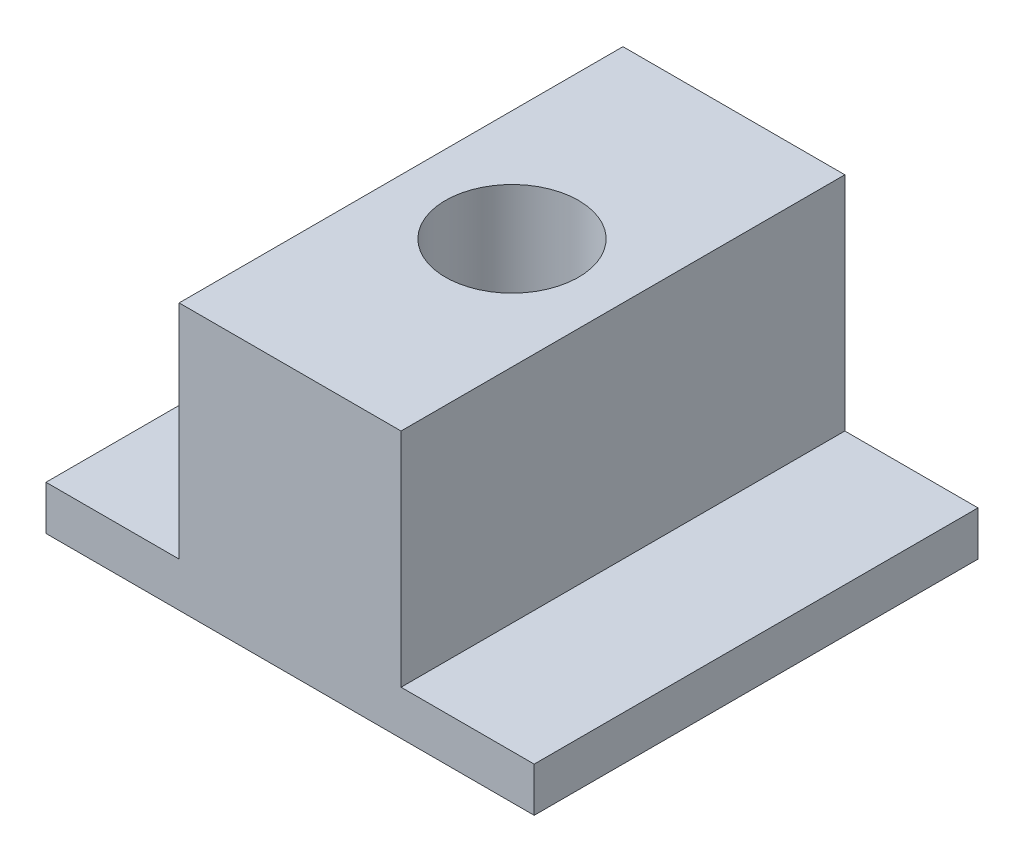
SolidWorks part; units mm, degrees
ref_plane "Front Plane" through (0, 0, 0) normal (0, 0, 1) x (1, 0, 0)
ref_plane "Top Plane" through (0, 0, 0) normal (0, 1, 0) x (1, 0, 0)
ref_plane "Right Plane" through (0, 0, 0) normal (1, 0, 0) x (0, 0, -1)
sketch "Sketch1" plane through (0, 0, 0) normal (0, 1, 0) x (1, 0, 0)
  line L1 (-2.5, -5) -> (2.5, -5)
  line L2 (-2.5, -5) -> (-2.5, 5)
  line L3 (-2.5, 5) -> (2.5, 5)
  line L4 (2.5, -5) -> (2.5, 5)
  line L5 (-2.5, -5) -> (2.5, 5) construction
  line L6 (-2.5, 5) -> (2.5, -5) construction
  point P0 (0, 0)
  dimension "D1" = 5
  dimension "D2" = 10
extrude "Boss-Extrude1" add sketch "Sketch1" along normal blind 5
sketch "Sketch2" plane through (0, 0, 0) normal (0, -1, 0) x (1, 0, 0)
  line L1 (-5.5, 5) -> (5.5, 5)
  line L2 (-5.5, 5) -> (-5.5, -5)
  line L3 (-5.5, -5) -> (5.5, -5)
  line L4 (5.5, 5) -> (5.5, -5)
  line L5 (-5.5, 5) -> (5.5, -5) construction
  line L6 (-5.5, -5) -> (5.5, 5) construction
  point P0 (0, 0)
  dimension "D1" = 10
  dimension "D2" = 11
extrude "Boss-Extrude2" add sketch "Sketch2" along normal blind 1
sketch "Sketch3" plane through (0, -1, 0) normal (0, -1, 0) x (1, 0, 0)
  circle A0 centre (0, 0) radius 1.5
  dimension "D1" = 3
extrude "Cut-Extrude1" cut sketch "Sketch3" against normal through all
